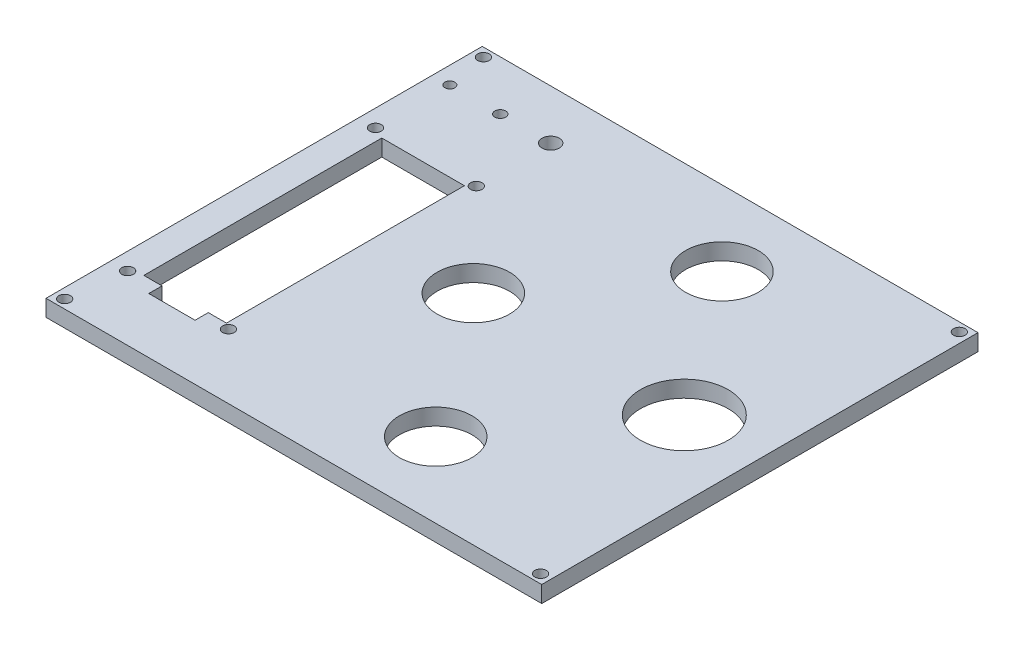
SolidWorks part; units mm, degrees
ref_plane "Front Plane" through (0, 0, 0) normal (0, 0, 1) x (1, 0, 0)
ref_plane "Top Plane" through (0, 0, 0) normal (0, 1, 0) x (1, 0, 0)
ref_plane "Right Plane" through (0, 0, 0) normal (1, 0, 0) x (0, 0, -1)
sketch "Sketch1" plane through (0, 0, 0) normal (0, 1, 0) x (1, 0, 0)
  line L0 (75, 66) -> (-75, -66) construction
  line L1 (-75, 66) -> (75, 66)
  line L2 (-75, 66) -> (-75, -66)
  line L3 (-75, -66) -> (75, -66)
  line L4 (75, 66) -> (75, -66)
  line L5 (0, -66) -> (0, 66) construction
  line L6 (-75, 0) -> (75, 0) construction
  line L7 (75, -66) -> (-75, 66) construction
  circle A2 centre (71.9971, 63.3575) radius 1.75
  circle A3 centre (71.9971, -63.3575) radius 1.75
  circle A4 centre (-71.9971, 63.3575) radius 1.75
  circle A5 centre (-71.9971, -63.3575) radius 1.75
  point P120 (0, 0)
  dimension "D3" = 3.5
  dimension "D4" = 4
  dimension "D1" = 132
  dimension "D2" = 150
extrude "Boss-Extrude1" add sketch "Sketch1" along normal blind 5
sketch "Sketch2" plane through (0, 0, 0) normal (0, -1, 0) x (1, 0, 0)
  line L0 (-75, -66) -> (-75, 66) construction
  line L1 (-36, 49) -> (-72, 49) construction
  line L2 (-36, 49) -> (-36, -31) construction
  line L3 (-36, -31) -> (-72, -31) construction
  line L4 (-72, 49) -> (-72, -31) construction
  line L5 (-54, -31) -> (-54, 49) construction
  line L6 (-36, 9) -> (-72, 9) construction
  line L7 (-39.3, 46.5) -> (-69.8, 46.5) construction
  line L8 (75, -66) -> (-75, -66) construction
  line L9 (-69.8, 46.5) -> (-69.8, -28.5) construction
  line L10 (-69.8, -28.5) -> (-39.3, -28.5) construction
  line L11 (-39.3, -28.5) -> (-39.3, 46.5) construction
  line L12 (-53.7, 45.2) -> (-54, 45.2)
  line L13 (-41.2, 45.2) -> (-46.7, 45.2)
  line L14 (-41.2, 45.2) -> (-41.2, -26.8)
  line L15 (-41.2, -26.8) -> (-66.2, -26.8)
  line L16 (-66.2, 45.2) -> (-66.2, -26.8)
  line L17 (-53.7, -26.8) -> (-53.7, 45.2) construction
  line L18 (-41.2, 9.2) -> (-66.2, 9.2) construction
  line L19 (-53.7, 45.2) -> (-54, 45.2)
  line L20 (-46.7, 45.2) -> (-46.7, 49.2)
  line L21 (-46.7, 49.2) -> (-60.7, 49.2)
  line L22 (-60.7, 45.2) -> (-60.7, 49.2)
  line L23 (-53.7, 49.2) -> (-53.7, 45.2) construction
  line L24 (-46.7, 47.2) -> (-60.7, 47.2) construction
  line L25 (-60.7, 45.2) -> (-66.2, 45.2)
  circle A0 centre (-39.3, 46.5) radius 1.75
  circle A1 centre (-39.3, -28.5) radius 1.75
  circle A2 centre (-69.8, 46.5) radius 1.75
  circle A3 centre (-69.8, -28.5) radius 1.75
  point P168 (-54, 9)
  point P181 (-53.7, 47.2)
  point P237 (-53.7, 9.2)
  dimension "D5" = 3.5
  dimension "D6" = 75
  dimension "D7" = 2.2
  dimension "D8" = 3.5
  dimension "D9" = 3.5
  dimension "D10" = 30.5
  dimension "D1" = 80
  dimension "D2" = 36
  dimension "D3" = 3
  dimension "D4" = 35
  dimension "D11" = 72
  dimension "D12" = 25
  dimension "D13" = 5.2
  dimension "D14" = 4.2
  dimension "D15" = 4
  dimension "D16" = 14
  dimension "D17" = 5.5
extrude "Cut-Extrude1" cut sketch "Sketch2" against normal blind 5
sketch "Sketch3" plane through (0, 5, 0) normal (0, 1, 0) x (1, 0, 0)
  line L1 (-69.8, 28.5) -> (-69.8, 51) construction
  line L2 (-39.3, 51) -> (-54.55, 51) construction
  line L3 (-54.55, 51) -> (-69.8, 51) construction
  line L5 (75, 66) -> (-75, 66) construction
  line L6 (-39.3, 28.5) -> (-39.3, 51) construction
  circle A0 centre (-69.8, 51) radius 1.5
  circle A1 centre (-54.55, 51) radius 1.64
  circle A2 centre (-39.3, 51) radius 2.61
  dimension "D1" = 3
  dimension "D2" = 3.28
  dimension "D3" = 5.22
  dimension "D4" = 15
  dimension "D5" = 15.25
extrude "Cut-Extrude2" cut sketch "Sketch3" against normal blind 5
sketch "Sketch4" plane through (0, 5, 0) normal (0, 1, 0) x (1, 0, 0)
  line L0 (-11.7, 0) -> (52.1356, 0) construction
  line L1 (3, 22.1) -> (-26.4, 22.1) construction
  line L2 (3, 22.1) -> (3, -22.1) construction
  line L3 (3, -22.1) -> (-26.4, -22.1) construction
  line L4 (-26.4, 22.1) -> (-26.4, -22.1) construction
  line L5 (-11.7, -22.1) -> (-11.7, 22.1) construction
  line L6 (3, 0) -> (-26.4, 0) construction
  line L7 (35.6356, -16.5) -> (68.6356, -16.5) construction
  line L8 (35.6356, -16.5) -> (35.6356, 16.5) construction
  line L9 (35.6356, 16.5) -> (68.6356, 16.5) construction
  line L10 (68.6356, -16.5) -> (68.6356, 16.5) construction
  line L11 (35.6356, -16.5) -> (68.6356, 16.5) construction
  line L12 (35.6356, 16.5) -> (68.6356, -16.5) construction
  line L13 (-1.8822, -28.6) -> (42.3178, -28.6) construction
  line L14 (-1.8822, -28.6) -> (-1.8822, -58) construction
  line L15 (-1.8822, -58) -> (42.3178, -58) construction
  line L16 (42.3178, -28.6) -> (42.3178, -58) construction
  line L17 (-1.8822, -28.6) -> (42.3178, -58) construction
  line L18 (-1.8822, -58) -> (42.3178, -28.6) construction
  line L19 (-1.8822, 28.6) -> (42.3178, 28.6) construction
  line L20 (-1.8822, 28.6) -> (-1.8822, 58) construction
  line L21 (-1.8822, 58) -> (42.3178, 58) construction
  line L22 (42.3178, 28.6) -> (42.3178, 58) construction
  line L23 (-1.8822, 28.6) -> (42.3178, 58) construction
  line L24 (-1.8822, 58) -> (42.3178, 28.6) construction
  line L25 (20.2178, 43.3) -> (20.2178, -43.3) construction
  line L27 (75, 66) -> (-75, 66) construction
  line L28 (75, -66) -> (75, 66) construction
  line L29 (-75, -66) -> (75, -66) construction
  circle A0 centre (-11.7, 0) radius 10.975
  circle A1 centre (20.2178, 43.3) radius 10.975
  circle A2 centre (20.2178, -43.3) radius 10.975
  circle A3 centre (52.1356, 0) radius 13.275
  circle A4 centre (52.1356, 0) radius 17.5 construction
  point P24 (20.2178, 0)
  point P25 (20.2178, 0)
  point P132 (-11.7, 0)
  dimension "D1" = 21.95
  dimension "D2" = 21.95
  dimension "D3" = 21.95
  dimension "D4" = 8
  dimension "D5" = 44.2
  dimension "D16" = 26.55
  dimension "D17" = 35
  dimension "D6" = 29.4
  dimension "D7" = 33
  dimension "D8" = 33
  dimension "D9" = 29.4
  dimension "D10" = 44.2
  dimension "D11" = 29.4
  dimension "D12" = 44.2
  dimension "D13" = 32.6822
  dimension "D14" = 8
  dimension "D15" = 72
extrude "Cut-Extrude3" cut sketch "Sketch4" against normal blind 5
